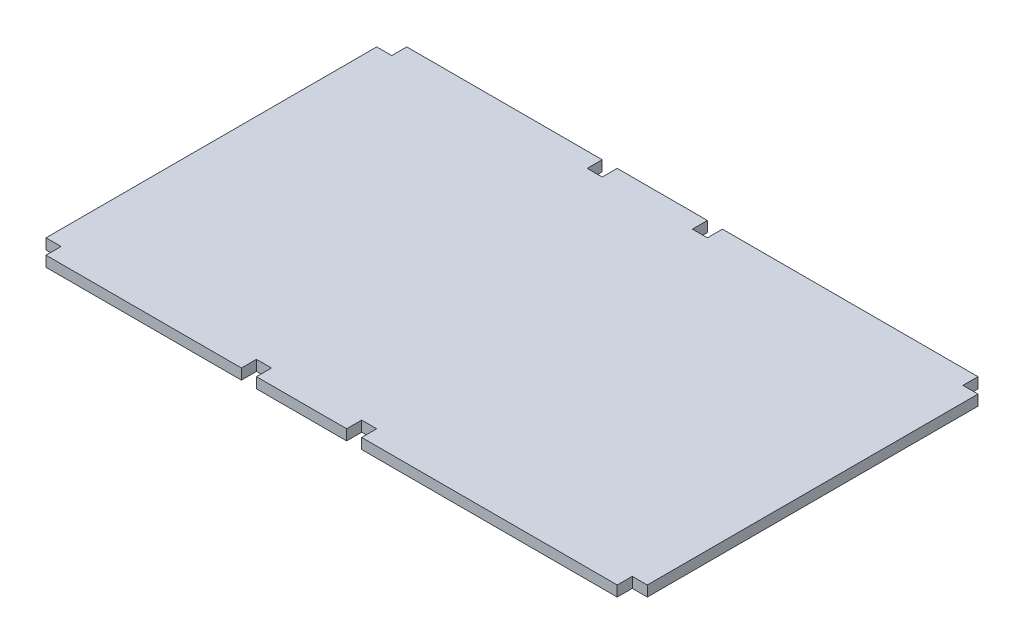
SolidWorks part; units mm, degrees
material "Teak"
ref_plane "Front Plane" through (0, 0, 0) normal (0, 0, 1) x (1, 0, 0)
ref_plane "Top Plane" through (0, 0, 0) normal (0, 1, 0) x (1, 0, 0)
ref_plane "Right Plane" through (0, 0, 0) normal (1, 0, 0) x (0, 0, -1)
sketch "Sketch1" plane through (0, 0, 0) normal (0, 1, 0) x (1, 0, 0)
  line L0 (-660.4, 609.6) -> (-990.6, 609.6)
  line L1 (-25.4, 0) -> (-457.184, 0)
  line L2 (0, 25.4) -> (0, 584.2)
  line L3 (-25.4, 609.6) -> (-457.184, 609.6)
  line L4 (-1016, 25.4) -> (-1016, 584.2)
  line L5 (-482.584, 609.6) -> (-635, 609.6)
  line L6 (-660.4, 584.2) -> (-635, 584.2)
  line L7 (0, 25.4) -> (-25.4, 25.4)
  line L8 (-25.4, 0) -> (-25.4, 25.4)
  line L9 (-660.4, 584.2) -> (-660.4, 609.6)
  line L10 (-660.4, 0) -> (-990.6, 0)
  line L11 (0, 584.2) -> (-25.4, 584.2)
  line L12 (-25.4, 609.6) -> (-25.4, 584.2)
  line L13 (-635, 584.2) -> (-635, 609.6)
  line L14 (-457.184, 584.2) -> (-482.584, 584.2)
  line L15 (-1016, 584.2) -> (-990.6, 584.2)
  line L16 (-990.6, 609.6) -> (-990.6, 584.2)
  line L17 (-457.184, 584.2) -> (-457.184, 609.6)
  line L19 (-1016, 25.4) -> (-990.6, 25.4)
  line L20 (-990.6, 0) -> (-990.6, 25.4)
  line L21 (-482.584, 584.2) -> (-482.584, 609.6)
  line L22 (-457.184, 0) -> (-457.184, 25.4)
  line L23 (-457.184, 25.4) -> (-482.584, 25.4)
  line L24 (-482.584, 0) -> (-482.584, 25.4)
  line L25 (-482.584, 0) -> (-635, 0)
  line L26 (-635, 0) -> (-635, 25.4)
  line L27 (-635, 25.4) -> (-660.4, 25.4)
  line L28 (-660.4, 0) -> (-660.4, 25.4)
  dimension "D3" = 25.4
  dimension "D4" = 25.4
  dimension "D5" = 25.4
  dimension "D6" = 25.4
  dimension "D7" = 25.4
  dimension "D8" = 25.4
  dimension "D9" = 25.4
extrude "Boss-Extrude1" add sketch "Sketch1" along normal blind 17.78
